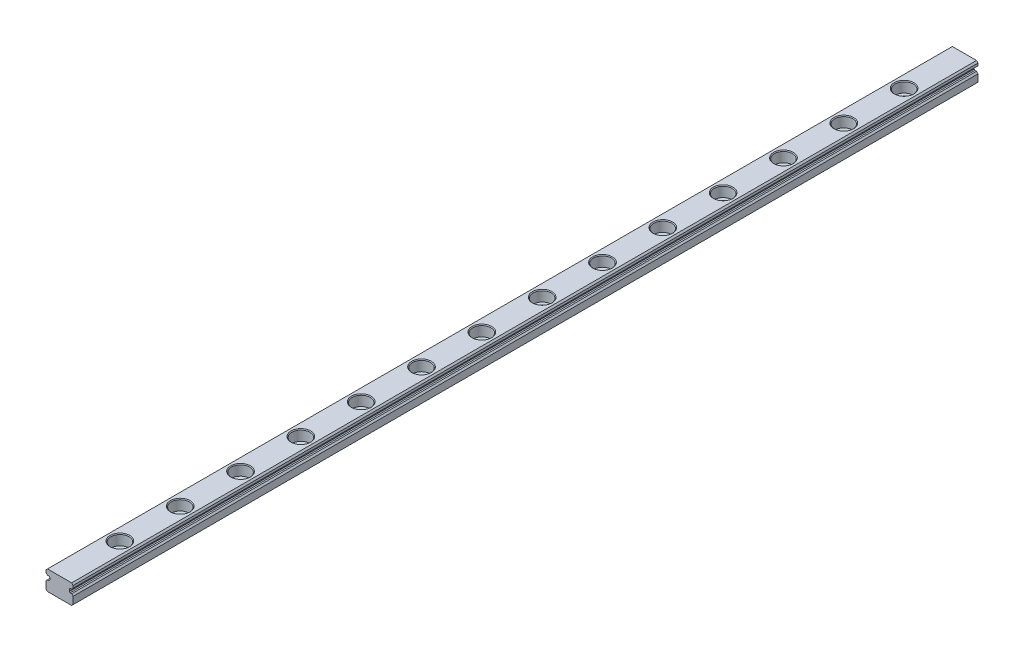
SolidWorks part; units mm, degrees
ref_plane "前视基准面" through (0, 0, 0) normal (0, 0, 1) x (1, 0, 0)
ref_plane "上视基准面" through (0, 0, 0) normal (0, 1, 0) x (1, 0, 0)
ref_plane "右视基准面" through (0, 0, 0) normal (1, 0, 0) x (0, 0, -1)
sketch "Sketch1" plane through (0, 0, 0) normal (0, 0, 1) x (1, 0, 0)
  line L0 (-4.005, 6.5) -> (4.005, 6.5)
  line L1 (4.005, 6.5) -> (4.5, 6.005)
  line L2 (4.5, 6.005) -> (4.5, 5.205)
  line L3 (4.5, 5.205) -> (4.005, 4.7101)
  line L4 (4.005, 4.7101) -> (3.5101, 4.7101)
  line L5 (3.5101, 4.7101) -> (3.25, 4.45)
  line L6 (3.25, 4.45) -> (3.25, 3.65)
  line L7 (3.25, 3.65) -> (3.5101, 3.3899)
  line L8 (3.5101, 3.3899) -> (4.005, 3.3899)
  line L9 (4.005, 3.3899) -> (4.5, 2.895)
  line L10 (4.5, 2.895) -> (4.5, 0.495)
  line L11 (4.5, 0.495) -> (4.005, 0)
  line L12 (4.005, 0) -> (-4.005, 0)
  line L13 (0, 0) -> (0, 6.5) construction
  line L14 (-4.5, 0.495) -> (-4.005, 0)
  line L15 (-4.5, 2.895) -> (-4.5, 0.495)
  line L16 (-4.005, 3.3899) -> (-4.5, 2.895)
  line L17 (-3.5101, 3.3899) -> (-4.005, 3.3899)
  line L18 (-3.25, 3.65) -> (-3.5101, 3.3899)
  line L19 (-3.25, 4.45) -> (-3.25, 3.65)
  line L20 (-3.5101, 4.7101) -> (-3.25, 4.45)
  line L21 (-4.005, 4.7101) -> (-3.5101, 4.7101)
  line L22 (-4.5, 5.205) -> (-4.005, 4.7101)
  line L23 (-4.5, 6.005) -> (-4.5, 5.205)
  line L24 (-4.005, 6.5) -> (-4.5, 6.005)
  point P11 (0, 0)
  point P15 (4.2805, 6.1225)
  point P16 (0, 0)
  point P17 (0, 0)
  point P18 (0, 0)
  point P19 (0, 0)
  point P21 (2.3186, 4.5302)
  point P22 (0, 0)
  point P23 (2.3897, 4.6155)
  point P24 (4.0388, 4.5729)
  point P25 (2.443, 4.3719)
  point P38 (2.4429, 4.1479)
  dimension "D1" = 6.5
  dimension "D2" = 4.5
  dimension "D3" = 0.8
  dimension "D4" = 135
  dimension "D5" = 0.7
  dimension "D6" = 6.5
  dimension "D7" = 2.4
  dimension "D8" = 0.8
extrude "Boss-Extrude1" add sketch "Sketch1" along normal blind 300
sketch "Sketch2" plane through (0, 6.5, 0) normal (0, 1, 0) x (1, 0, 0)
  circle A0 centre (0, -20) radius 3
  circle A1 centre (0, -40) radius 3
  circle A2 centre (0, -60) radius 3
  circle A3 centre (0, -80) radius 3
  circle A4 centre (0, -100) radius 3
  circle A5 centre (0, -120) radius 3
  circle A6 centre (0, -140) radius 3
  circle A7 centre (0, -160) radius 3
  circle A8 centre (0, -180) radius 3
  circle A9 centre (0, -200) radius 3
  circle A10 centre (0, -220) radius 3
  circle A11 centre (0, -240) radius 3
  circle A12 centre (0, -260) radius 3
  circle A13 centre (0, -280) radius 3
  dimension "D1" = 6
  dimension "D2" = 20
  dimension "D3" = 14
hole_wizard "CBORE for M3 Pan Head Screw1" positions "3DSketch1" profile "Sketch3" counterbore size "M3" standard "JIS" end condition through all
sketch3d "3DSketch1"
  point P0 (0, 6.5, 20)
  point P3 (0, 6.5, 40)
sketch "Sketch3" plane through (0, 6.5, 20) normal (1, 0, 0) x (0, 0, 1)
  line L0 (0, 0) -> (0, 6.5)
  line L1 (0, 6.5) -> (1.75, 6.5)
  line L3 (1.75, 6.5) -> (1.75, 3.5)
  line L4 (3, 3.5) -> (1.75, 3.5)
  line L5 (3, 3.5) -> (3, 0.25)
  line L6 (3, 0.25) -> (3.25, 0)
  line L7 (3.25, 0) -> (0, 0)
  line L8 (-3, 0.25) -> (-3.25, 0) construction
  line L11 (0, -6.35) -> (0, 107.95) construction
  dimension "Thru Hole Dia." = 3.5
  dimension "Thru Hole Depth" = 6.5
  dimension "C'Bore Dia." = 6
  dimension "C'Bore Depth" = 3.5
  dimension "Near C'Sink Dia." = 6.5
  dimension "Near C'Sink Angle" = 90
pattern_linear "LPattern1" count 13 spacing 20 along (0, 0, 1) of "CBORE for M3 Pan Head Screw1"
